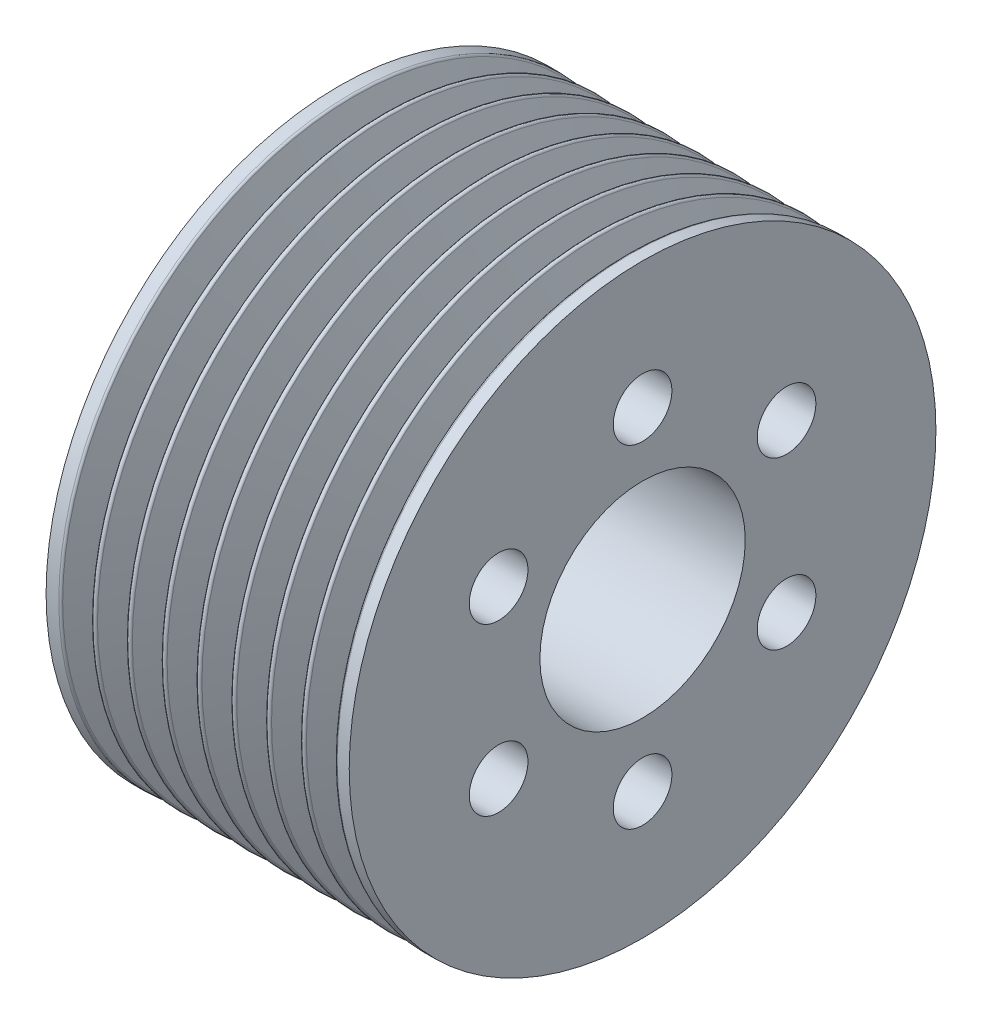
SolidWorks part; units mm, degrees
material "2018 Alloy"
ref_plane "Front Plane" through (0, 0, 0) normal (0, 0, 1) x (1, 0, 0)
ref_plane "Top Plane" through (0, 0, 0) normal (0, 1, 0) x (1, 0, 0)
ref_plane "Right Plane" through (0, 0, 0) normal (1, 0, 0) x (0, 0, -1)
sketch "Sketch1" plane through (0, 0, 0) normal (0, 0, 1) x (1, 0, 0)
  line L0 (49, 10.5) -> (49, 0) construction
  line L1 (49, 10.5) -> (49, 30)
  line L2 (49, 30) -> (18, 30)
  line L3 (18, 30) -> (18, 25)
  line L4 (49, 10.5) -> (31.5, 10.5)
  line L5 (0, 0) -> (49, 0) construction
  line L6 (18, 25) -> (31.5, 25)
  line L8 (0, 8.3175) -> (0, 0) construction
  line L9 (31.5, 10.5) -> (31.5, 25)
  dimension "D1" = 31
  dimension "D2" = 60
  dimension "D3" = 31.5
  dimension "D4" = 50
  dimension "D5" = 49
  dimension "D8" = 21
revolve "Revolve1" add sketch "Sketch1" angle 360 about L5
sketch "Sketch2" plane through (0, 0, 0) normal (0, 0, 1) x (1, 0, 0)
  line L0 (47.5451, 29.8355) -> (46.2819, 26.365)
  line L1 (45.7181, 26.365) -> (44.4549, 29.8355)
  line L2 (47.5451, 29.8355) -> (47.6049, 30) construction
  line L3 (49, 30) -> (18, 30) construction
  line L4 (44.4549, 29.8355) -> (44.3951, 30) construction
  line L5 (49, -30) -> (49, 30) construction
  line L6 (47.78, 30) -> (44.22, 30)
  line L7 (0, 0) -> (49, 0) construction
  arc A0 (47.5451, 29.8355) -> (47.78, 30) centre (47.78, 29.75) cw
  arc A1 (44.4549, 29.8355) -> (44.22, 30) centre (44.22, 29.75) ccw
  arc A2 (46.2819, 26.365) -> (45.7181, 26.365) centre (46, 26.4676) cw
  dimension "D2" = 0.25
  dimension "D3" = 0.3
  dimension "D1" = 40
  dimension "D4" = 3.56
  dimension "D5" = 3
revolve "Cut-Revolve1" cut sketch "Sketch2" angle 360 about L7
pattern_linear "LPattern1" count 8 spacing 3.56 along (-1, 0, 0) of "Cut-Revolve1"
sketch "Sketch3" plane through (49, 0, 0) normal (1, 0, 0) x (0, 0, -1)
  circle A0 centre (0, 0) radius 17 construction
  circle A1 centre (0, 17) radius 3
  circle A2 centre (14.7224, 8.5) radius 3
  circle A3 centre (14.7224, -8.5) radius 3
  circle A4 centre (0, -17) radius 3
  circle A5 centre (-14.7224, -8.5) radius 3
  circle A6 centre (-14.7224, 8.5) radius 3
  dimension "D1" = 34
  dimension "D2" = 6
  dimension "D3" = 6
extrude "Cut-Extrude1" cut sketch "Sketch3" against normal up to surface (17.5 mm away) up to face at (31.5, 0, 10.5)
